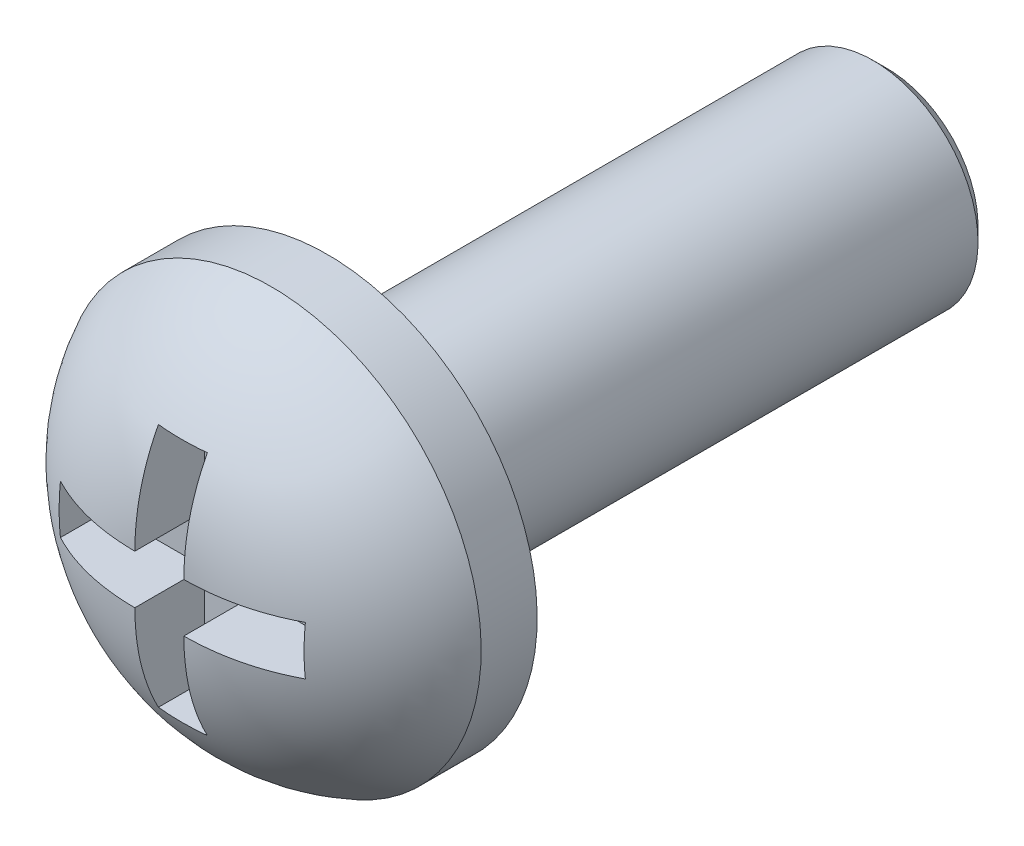
SolidWorks part; units mm, degrees
ref_plane "Front" through (0, 0, 0) normal (0, 0, 1) x (1, 0, 0)
ref_plane "Top" through (0, 0, 0) normal (0, 1, 0) x (1, 0, 0)
ref_plane "Right" through (0, 0, 0) normal (1, 0, 0) x (0, 0, -1)
sketch "Croquis1" plane through (0, 0, 0) normal (1, 0, 0) x (0, 0, -1)
  line L0 (0, 3) -> (0, 1.5)
  line L1 (-0.8, 3) -> (0, 3)
  line L2 (0, 1.5) -> (8, 1.5)
  line L3 (8, 1.5) -> (8, 0)
  line L5 (8, 0) -> (-2.4, 0)
  line L7 (-2.4, 0) -> (-2.4, 0.4388)
  line L9 (8, 0) -> (11.2578, 0) construction
  arc A1 (-0.8, 3) -> (-2.4, 0.4388) centre (0.45, 0.4388) ccw
  dimension "D4" = 2.85
  dimension "D1" = 8
  dimension "D2" = 2.4
  dimension "D3" = 3
  dimension "D5" = 0.8
  dimension "D6" = 6
revolve "Revolución1" add sketch "Croquis1" angle 360 about L9
sketch "Croquis2" plane through (0, 0, 2.4) normal (0, 0, 1) x (1, 0, 0)
  line L0 (-0.35, 0.35) -> (-1.75, 0.35)
  line L1 (1.75, -0.35) -> (0.35, -0.35)
  line L2 (1.75, -0.35) -> (1.75, 0.35)
  line L3 (1.75, 0.35) -> (0.35, 0.35)
  line L4 (-1.75, -0.35) -> (-1.75, 0.35)
  line L5 (1.75, -0.35) -> (-1.75, 0.35) construction
  line L6 (1.75, 0.35) -> (-1.75, -0.35) construction
  line L7 (-0.35, -1.75) -> (0.35, -1.75)
  line L8 (-0.35, -1.75) -> (-0.35, -0.35)
  line L9 (-0.35, 1.75) -> (0.35, 1.75)
  line L10 (0.35, -1.75) -> (0.35, -0.35)
  line L11 (-0.35, -1.75) -> (0.35, 1.75) construction
  line L12 (-0.35, 1.75) -> (0.35, -1.75) construction
  line L13 (0.35, 0.35) -> (0.35, 1.75)
  line L14 (-0.35, -0.35) -> (-1.75, -0.35)
  line L15 (-0.35, 0.35) -> (-0.35, 1.75)
  point P0 (0, 0)
  point P5 (0, 0)
  dimension "D1" = 0.7
  dimension "D2" = 3.5
  dimension "D3" = 3.5
extrude "Cortar-Extruir2" cut sketch "Croquis2" against normal blind 1
chamfer "Chaflán1" distance 0.2 angle 45 1 edges at (0, -1.5, -8)
